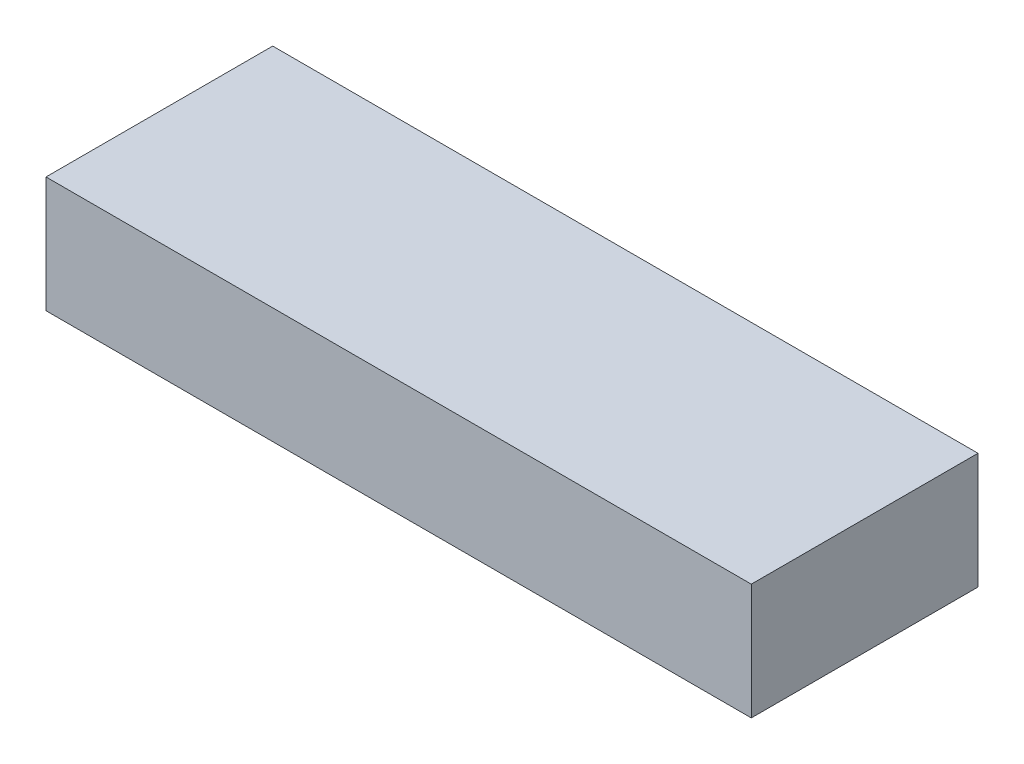
SolidWorks part; units mm, degrees
ref_plane "Front Plane" through (0, 0, 0) normal (0, 0, 1) x (1, 0, 0)
ref_plane "Top Plane" through (0, 0, 0) normal (0, 1, 0) x (1, 0, 0)
ref_plane "Right Plane" through (0, 0, 0) normal (1, 0, 0) x (0, 0, -1)
sketch "Sketch1" plane through (0, 0, 0) normal (0, 1, 0) x (1, 0, 0)
  line L1 (-70, -22.5) -> (70, -22.5)
  line L2 (-70, -22.5) -> (-70, 22.5)
  line L3 (-70, 22.5) -> (70, 22.5)
  line L4 (70, -22.5) -> (70, 22.5)
  line L5 (-70, -22.5) -> (70, 22.5) construction
  line L6 (-70, 22.5) -> (70, -22.5) construction
  point P0 (0, 0)
  dimension "D1" = 45
  dimension "D2" = 140
extrude "Boss-Extrude1" add sketch "Sketch1" along normal blind 23
